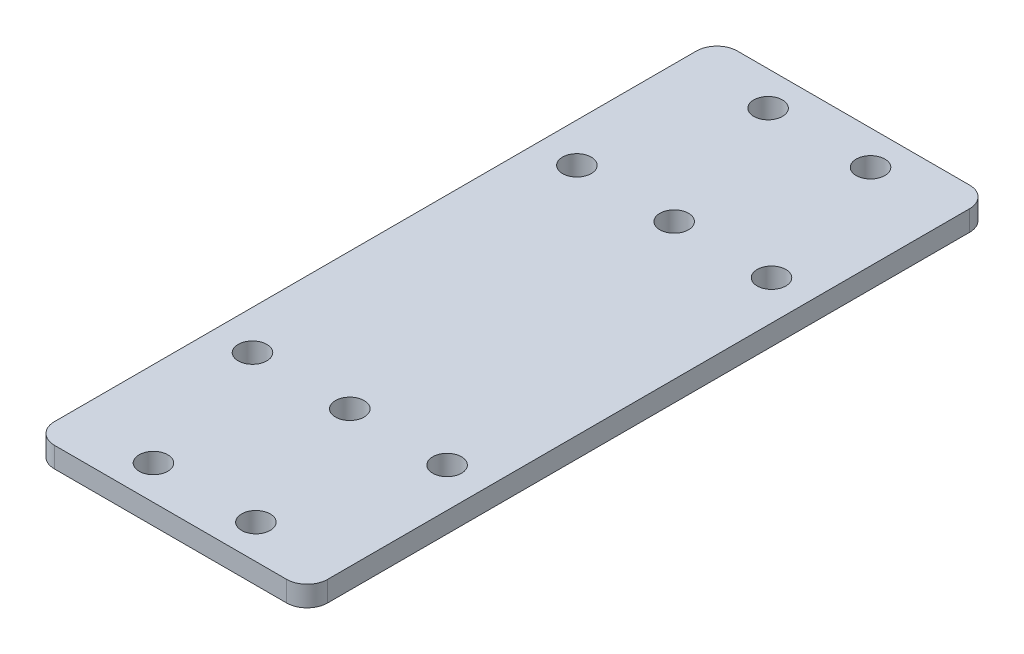
SolidWorks part; units mm, degrees
material "ｱｸﾘﾙ (中-上級の耐衝撃性)"
ref_plane "正面" through (0, 0, 0) normal (0, 0, 1) x (1, 0, 0)
ref_plane "平面" through (0, 0, 0) normal (0, 1, 0) x (1, 0, 0)
ref_plane "右側面" through (0, 0, 0) normal (1, 0, 0) x (0, 0, -1)
sketch "ｽｹｯﾁ1" plane through (0, 0, 0) normal (0, 1, 0) x (1, 0, 0)
  line L0 (0, 23.75) -> (0, 0) construction
  line L1 (-20, 50) -> (20, 50)
  line L2 (-20, 50) -> (-20, -50)
  line L3 (-20, -50) -> (20, -50)
  line L4 (20, 50) -> (20, -50)
  line L5 (-20, 50) -> (20, -50) construction
  line L6 (-20, -50) -> (20, 50) construction
  line L7 (-14.25, 23.75) -> (14.25, 23.75) construction
  line L8 (-14.25, 23.75) -> (-14.25, -23.75) construction
  line L9 (-14.25, -23.75) -> (14.25, -23.75) construction
  line L10 (14.25, 23.75) -> (14.25, -23.75) construction
  line L11 (-14.25, 23.75) -> (14.25, -23.75) construction
  line L12 (-14.25, -23.75) -> (14.25, 23.75) construction
  line L13 (0, 0) -> (14.25, 0) construction
  circle A0 centre (14.25, 23.75) radius 2.1
  circle A1 centre (-14.25, 23.75) radius 2.1
  circle A2 centre (-14.25, -23.75) radius 2.1
  circle A3 centre (14.25, -23.75) radius 2.1
  circle A4 centre (7.5, 45) radius 2.1
  circle A5 centre (-7.5, 45) radius 2.1
  circle A6 centre (-7.5, -45) radius 2.1
  circle A7 centre (7.5, -45) radius 2.1
  circle A8 centre (0, 23.75) radius 2.1
  circle A9 centre (0, -23.75) radius 2.1
  point P0 (0, 0)
  point P6 (0, 0)
  dimension "D4" = 4.2
  dimension "D1" = 100
  dimension "D2" = 28.5
  dimension "D3" = 47.5
  dimension "D5" = 5
  dimension "D6" = 15
  dimension "D7" = 40
extrude "ﾎﾞｽ - 押し出し1" add sketch "ｽｹｯﾁ1" along normal blind 3
fillet "ﾌｨﾚｯﾄ1" radius 3 4 edges at (-20, 1.5, -50) (20, 1.5, -50) (20, 1.5, 50) (-20, 1.5, 50)
